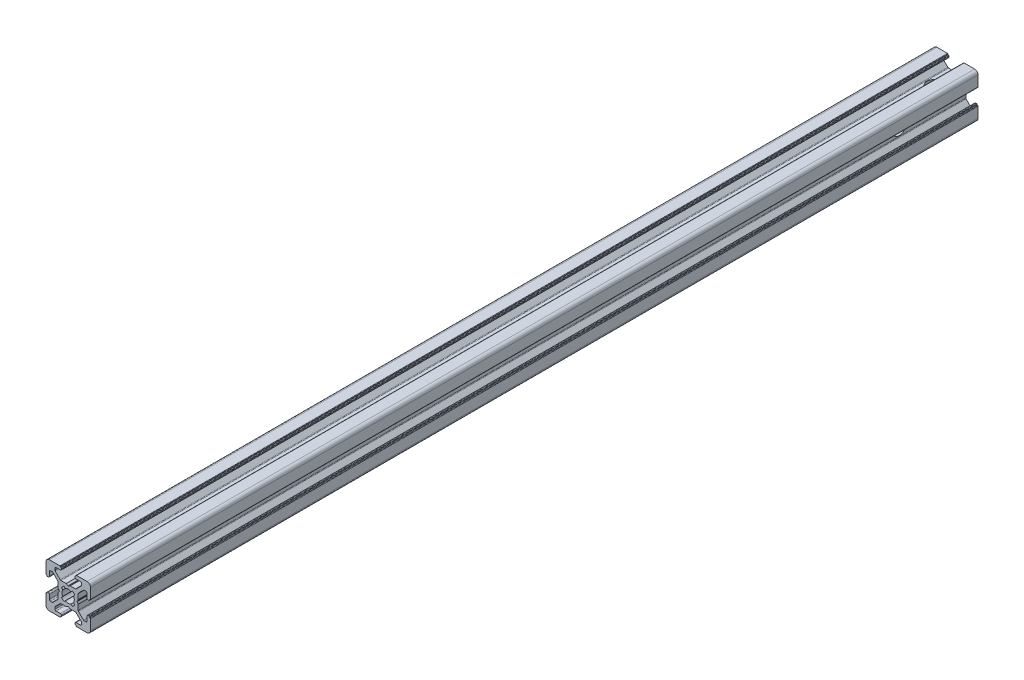
SolidWorks part; units mm, degrees
ref_plane "Front Plane" through (0, 0, 0) normal (0, 0, 1) x (1, 0, 0)
ref_plane "Top Plane" through (0, 0, 0) normal (0, 1, 0) x (1, 0, 0)
ref_plane "Right Plane" through (0, 0, 0) normal (1, 0, 0) x (0, 0, -1)
sketch "Sketch1" plane through (0, 0, 0) normal (0, 0, 1) x (1, 0, 0)
  line L0 (0, 13.3675) -> (0, -10.9159) construction
  line L1 (-12.9725, 0) -> (15.1887, 0) construction
  line L2 (-3.5, 8.5) -> (-5.5, 8.5)
  line L3 (-3.55, 9.7) -> (-3.55, 9.8)
  line L4 (-6, 7.2678) -> (-6, 8)
  line L5 (-7.2678, 6) -> (-8, 6)
  line L6 (-3.75, 10) -> (-8.5, 10)
  line L7 (-9.7, 3.55) -> (-9.8, 3.55)
  line L8 (-9.5, 3.2) -> (-9.5, 3.35)
  line L9 (-9, 3) -> (-9.3, 3)
  line L10 (-4.4732, 0.8536) -> (-4.0381, 0.1)
  line L11 (-4.5, 3.2322) -> (-4.5, 0.9536)
  line L12 (-8.5, 3.5) -> (-8.5, 5.5)
  line L13 (-10, 3.75) -> (-10, 8.5)
  line L14 (-3.5858, 4.6464) -> (-5.8536, 6.9142)
  line L15 (-4.6464, 3.5858) -> (-6.9142, 5.8536)
  line L16 (-3.2, 9.5) -> (-3.35, 9.5)
  line L17 (-3, 9) -> (-3, 9.3)
  line L18 (-0.8536, 4.4732) -> (-0.1, 4.0381)
  line L19 (-3.2322, 4.5) -> (-0.9536, 4.5)
  line L20 (-1.2582, 2.4453) -> (-1.9139, 2.9896)
  line L21 (-2.4453, 1.2582) -> (-2.9922, 1.9099)
  line L22 (3.5, -8.5) -> (5.5, -8.5)
  line L23 (3.55, -9.7) -> (3.55, -9.8)
  line L24 (6, -7.2678) -> (6, -8)
  line L25 (7.2678, -6) -> (8, -6)
  line L26 (3.75, -10) -> (8.5, -10)
  line L27 (9.7, -3.55) -> (9.8, -3.55)
  line L28 (9.5, -3.2) -> (9.5, -3.35)
  line L29 (9, -3) -> (9.3, -3)
  line L30 (4.4732, -0.8536) -> (4.0381, -0.1)
  line L31 (4.5, -3.2322) -> (4.5, -0.9536)
  line L32 (8.5, -3.5) -> (8.5, -5.5)
  line L33 (10, -3.75) -> (10, -8.5)
  line L34 (3.5858, -4.6464) -> (5.8536, -6.9142)
  line L35 (4.6464, -3.5858) -> (6.9142, -5.8536)
  line L36 (3.2, -9.5) -> (3.35, -9.5)
  line L37 (3, -9) -> (3, -9.3)
  line L38 (0.8536, -4.4732) -> (0.1, -4.0381)
  line L39 (3.2322, -4.5) -> (0.9536, -4.5)
  line L40 (1.2582, -2.4453) -> (1.9139, -2.9896)
  line L41 (2.4453, -1.2582) -> (2.9922, -1.9099)
  line L42 (-2.4453, -1.2582) -> (-2.9922, -1.9099)
  line L43 (-1.2582, -2.4453) -> (-1.9139, -2.9896)
  line L44 (-3.2322, -4.5) -> (-0.9536, -4.5)
  line L45 (-0.8536, -4.4732) -> (-0.1, -4.0381)
  line L46 (-3, -9) -> (-3, -9.3)
  line L47 (-3.2, -9.5) -> (-3.35, -9.5)
  line L48 (-4.6464, -3.5858) -> (-6.9142, -5.8536)
  line L49 (-3.5858, -4.6464) -> (-5.8536, -6.9142)
  line L50 (-10, -3.75) -> (-10, -8.5)
  line L51 (-8.5, -3.5) -> (-8.5, -5.5)
  line L52 (-4.5, -3.2322) -> (-4.5, -0.9536)
  line L53 (-4.4732, -0.8536) -> (-4.0381, -0.1)
  line L54 (-9, -3) -> (-9.3, -3)
  line L55 (-9.5, -3.2) -> (-9.5, -3.35)
  line L56 (-9.7, -3.55) -> (-9.8, -3.55)
  line L57 (2.4453, 1.2582) -> (2.9922, 1.9099)
  line L58 (1.2582, 2.4453) -> (1.9139, 2.9896)
  line L59 (3.2322, 4.5) -> (0.9536, 4.5)
  line L60 (0.8536, 4.4732) -> (0.1, 4.0381)
  line L61 (-3.75, -10) -> (-8.5, -10)
  line L62 (-7.2678, -6) -> (-8, -6)
  line L63 (-6, -7.2678) -> (-6, -8)
  line L64 (3, 9) -> (3, 9.3)
  line L65 (3.2, 9.5) -> (3.35, 9.5)
  line L66 (4.6464, 3.5858) -> (6.9142, 5.8536)
  line L67 (3.5858, 4.6464) -> (5.8536, 6.9142)
  line L68 (10, 3.75) -> (10, 8.5)
  line L69 (8.5, 3.5) -> (8.5, 5.5)
  line L70 (4.5, 3.2322) -> (4.5, 0.9536)
  line L71 (4.4732, 0.8536) -> (4.0381, 0.1)
  line L72 (9, 3) -> (9.3, 3)
  line L73 (9.5, 3.2) -> (9.5, 3.35)
  line L74 (9.7, 3.55) -> (9.8, 3.55)
  line L75 (3.75, 10) -> (8.5, 10)
  line L76 (7.2678, 6) -> (8, 6)
  line L77 (6, 7.2678) -> (6, 8)
  line L78 (3.55, 9.7) -> (3.55, 9.8)
  line L79 (3.5, 8.5) -> (5.5, 8.5)
  line L80 (-3.55, -9.7) -> (-3.55, -9.8)
  line L81 (-3.5, -8.5) -> (-5.5, -8.5)
  arc A0 (-10, 8.5) -> (-8.5, 10) centre (-8.5, 8.5) cw
  arc A1 (-8.5, 5.5) -> (-8, 6) centre (-8, 5.5) cw
  arc A2 (-7.2678, 6) -> (-6.9142, 5.8536) centre (-7.2678, 5.5) cw
  arc A3 (-5.8536, 6.9142) -> (-6, 7.2678) centre (-5.5, 7.2678) cw
  arc A4 (-6, 8) -> (-5.5, 8.5) centre (-5.5, 8) cw
  arc A5 (-9.7, 3.55) -> (-9.5, 3.35) centre (-9.7, 3.35) cw
  arc A6 (-9.8, 3.55) -> (-10, 3.75) centre (-9.8, 3.75) cw
  arc A7 (-9.3, 3) -> (-9.5, 3.2) centre (-9.3, 3.2) cw
  arc A8 (-8.5, 3.5) -> (-9, 3) centre (-9, 3.5) cw
  arc A9 (-4.6464, 3.5858) -> (-4.5, 3.2322) centre (-5, 3.2322) cw
  arc A10 (-4.4732, 0.8536) -> (-4.5, 0.9536) centre (-4.3, 0.9536) cw
  arc A11 (-4.0381, 0.1) -> (-4.0381, -0.1) centre (-4.2113, 0) cw
  arc A12 (-3.2, 9.5) -> (-3, 9.3) centre (-3.2, 9.3) cw
  arc A13 (-0.9536, 4.5) -> (-0.8536, 4.4732) centre (-0.9536, 4.3) cw
  arc A14 (-2.9922, 1.9099) -> (-1.9139, 2.9896) centre (0, 0) cw
  arc A15 (-3.2322, 4.5) -> (-3.5858, 4.6464) centre (-3.2322, 5) cw
  arc A16 (-3.75, 10) -> (-3.55, 9.8) centre (-3.75, 9.8) cw
  arc A17 (-3.35, 9.5) -> (-3.55, 9.7) centre (-3.35, 9.7) cw
  arc A18 (2.4453, -1.2582) -> (2.4453, 1.2582) centre (0, 0) ccw
  arc A19 (-3, 9) -> (-3.5, 8.5) centre (-3.5, 9) cw
  arc A20 (-2.4453, -1.2582) -> (-2.4453, 1.2582) centre (0, 0) cw
  arc A21 (10, -8.5) -> (8.5, -10) centre (8.5, -8.5) cw
  arc A22 (8.5, -5.5) -> (8, -6) centre (8, -5.5) cw
  arc A23 (7.2678, -6) -> (6.9142, -5.8536) centre (7.2678, -5.5) cw
  arc A24 (5.8536, -6.9142) -> (6, -7.2678) centre (5.5, -7.2678) cw
  arc A25 (6, -8) -> (5.5, -8.5) centre (5.5, -8) cw
  arc A26 (9.7, -3.55) -> (9.5, -3.35) centre (9.7, -3.35) cw
  arc A27 (9.8, -3.55) -> (10, -3.75) centre (9.8, -3.75) cw
  arc A28 (9.3, -3) -> (9.5, -3.2) centre (9.3, -3.2) cw
  arc A29 (8.5, -3.5) -> (9, -3) centre (9, -3.5) cw
  arc A30 (4.6464, -3.5858) -> (4.5, -3.2322) centre (5, -3.2322) cw
  arc A31 (4.4732, -0.8536) -> (4.5, -0.9536) centre (4.3, -0.9536) cw
  arc A32 (3.2, -9.5) -> (3, -9.3) centre (3.2, -9.3) cw
  arc A33 (-0.1, -4.0381) -> (0.1, -4.0381) centre (0, -4.2113) cw
  arc A34 (0.9536, -4.5) -> (0.8536, -4.4732) centre (0.9536, -4.3) cw
  arc A35 (2.9922, -1.9099) -> (1.9139, -2.9896) centre (0, 0) cw
  arc A36 (1.2582, -2.4453) -> (-1.2582, -2.4453) centre (0, 0) cw
  arc A37 (3.2322, -4.5) -> (3.5858, -4.6464) centre (3.2322, -5) cw
  arc A38 (3.75, -10) -> (3.55, -9.8) centre (3.75, -9.8) cw
  arc A39 (3.35, -9.5) -> (3.55, -9.7) centre (3.35, -9.7) cw
  arc A40 (3, -9) -> (3.5, -8.5) centre (3.5, -9) cw
  arc A41 (-3, -9) -> (-3.5, -8.5) centre (-3.5, -9) ccw
  arc A42 (-3.35, -9.5) -> (-3.55, -9.7) centre (-3.35, -9.7) ccw
  arc A43 (-3.75, -10) -> (-3.55, -9.8) centre (-3.75, -9.8) ccw
  arc A44 (-3.2322, -4.5) -> (-3.5858, -4.6464) centre (-3.2322, -5) ccw
  arc A45 (-2.9922, -1.9099) -> (-1.9139, -2.9896) centre (0, 0) ccw
  arc A46 (-0.9536, -4.5) -> (-0.8536, -4.4732) centre (-0.9536, -4.3) ccw
  arc A47 (-3.2, -9.5) -> (-3, -9.3) centre (-3.2, -9.3) ccw
  arc A48 (-4.4732, -0.8536) -> (-4.5, -0.9536) centre (-4.3, -0.9536) ccw
  arc A49 (3, 9) -> (3.5, 8.5) centre (3.5, 9) ccw
  arc A50 (3.35, 9.5) -> (3.55, 9.7) centre (3.35, 9.7) ccw
  arc A51 (3.75, 10) -> (3.55, 9.8) centre (3.75, 9.8) ccw
  arc A52 (3.2322, 4.5) -> (3.5858, 4.6464) centre (3.2322, 5) ccw
  arc A53 (1.2582, 2.4453) -> (-1.2582, 2.4453) centre (0, 0) ccw
  arc A54 (-4.6464, -3.5858) -> (-4.5, -3.2322) centre (-5, -3.2322) ccw
  arc A55 (-8.5, -3.5) -> (-9, -3) centre (-9, -3.5) ccw
  arc A56 (-9.3, -3) -> (-9.5, -3.2) centre (-9.3, -3.2) ccw
  arc A57 (-9.8, -3.55) -> (-10, -3.75) centre (-9.8, -3.75) ccw
  arc A58 (-9.7, -3.55) -> (-9.5, -3.35) centre (-9.7, -3.35) ccw
  arc A59 (-6, -8) -> (-5.5, -8.5) centre (-5.5, -8) ccw
  arc A60 (2.9922, 1.9099) -> (1.9139, 2.9896) centre (0, 0) ccw
  arc A61 (0.9536, 4.5) -> (0.8536, 4.4732) centre (0.9536, 4.3) ccw
  arc A62 (-0.1, 4.0381) -> (0.1, 4.0381) centre (0, 4.2113) ccw
  arc A63 (-5.8536, -6.9142) -> (-6, -7.2678) centre (-5.5, -7.2678) ccw
  arc A64 (-7.2678, -6) -> (-6.9142, -5.8536) centre (-7.2678, -5.5) ccw
  arc A65 (-8.5, -5.5) -> (-8, -6) centre (-8, -5.5) ccw
  arc A66 (-10, -8.5) -> (-8.5, -10) centre (-8.5, -8.5) ccw
  arc A67 (3.2, 9.5) -> (3, 9.3) centre (3.2, 9.3) ccw
  arc A68 (4.0381, 0.1) -> (4.0381, -0.1) centre (4.2113, 0) ccw
  arc A69 (4.4732, 0.8536) -> (4.5, 0.9536) centre (4.3, 0.9536) ccw
  arc A70 (4.6464, 3.5858) -> (4.5, 3.2322) centre (5, 3.2322) ccw
  arc A71 (8.5, 3.5) -> (9, 3) centre (9, 3.5) ccw
  arc A72 (9.3, 3) -> (9.5, 3.2) centre (9.3, 3.2) ccw
  arc A73 (9.8, 3.55) -> (10, 3.75) centre (9.8, 3.75) ccw
  arc A74 (9.7, 3.55) -> (9.5, 3.35) centre (9.7, 3.35) ccw
  arc A75 (6, 8) -> (5.5, 8.5) centre (5.5, 8) ccw
  arc A76 (5.8536, 6.9142) -> (6, 7.2678) centre (5.5, 7.2678) ccw
  arc A77 (7.2678, 6) -> (6.9142, 5.8536) centre (7.2678, 5.5) ccw
  arc A78 (8.5, 5.5) -> (8, 6) centre (8, 5.5) ccw
  arc A79 (10, 8.5) -> (8.5, 10) centre (8.5, 8.5) ccw
  dimension "D4" = 5.5
  dimension "D1" = 6
  dimension "D2" = 20
  dimension "D3" = 20
  dimension "D5" = 5.5
  dimension "D6" = 10
  dimension "D7" = 6
  dimension "D8" = 6
  dimension "D9" = 6
extrude "Extrude1" add sketch "Sketch1" along normal blind 400
sketch "Croquis1" plane through (0, -10, 0) normal (0, -1, 0) x (-1, 0, 0)
  line L0 (0, 0) -> (0, -10) construction
  line L1 (0, -10) -> (0, -12.5714) construction
  circle A0 centre (0, -10) radius 3
  dimension "D2" = 6
  dimension "D1" = 10
extrude "Barreno1" cut sketch "Croquis1" against normal blind 30
sketch "Croquis2" plane through (10, 0, 0) normal (1, 0, 0) x (0, 0, -1)
  line L0 (0, 0) -> (-30, 0) construction
  circle A0 centre (-30, 0) radius 3
  dimension "D2" = 6
  dimension "D1" = 30
extrude "Barreno2" cut sketch "Croquis2" against normal blind 30
